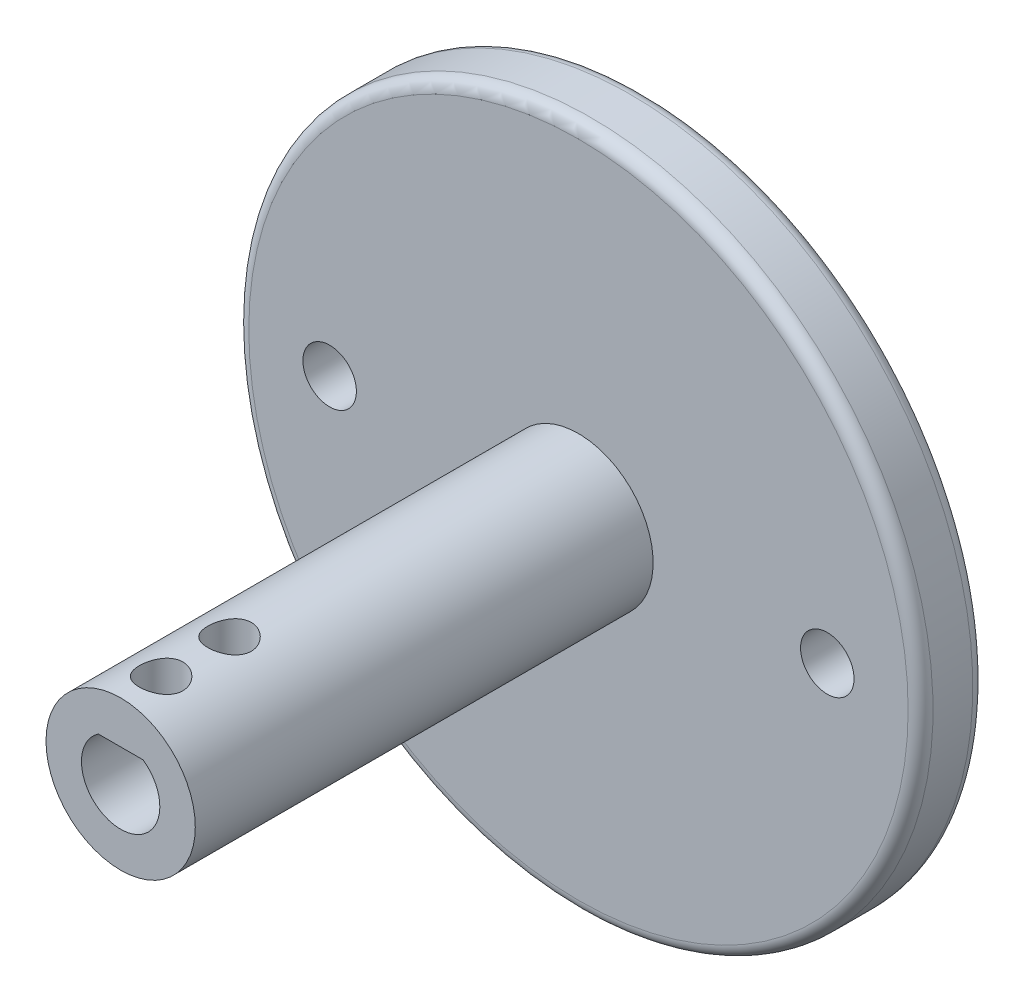
SolidWorks part; units mm, degrees
ref_plane "Alzado" through (0, 0, 0) normal (0, 0, 1) x (1, 0, 0)
ref_plane "Planta" through (0, 0, 0) normal (0, 1, 0) x (1, 0, 0)
ref_plane "Vista lateral" through (0, 0, 0) normal (1, 0, 0) x (0, 0, -1)
sketch "Croquis1" plane through (0, 0, 0) normal (0, 0, 1) x (1, 0, 0)
  line L0 (0, 0) -> (0, 2.5851) construction
  line L7 (-1.8, 2.5851) -> (1.8, 2.5851)
  circle A0 centre (0, 0) radius 6
  arc A1 (-1.8, 2.5851) -> (1.8, 2.5851) centre (0, 0) ccw
  point P14 (0, 2.5851)
  dimension "D2" = 6.3
  dimension "D1" = 12
  dimension "D3" = 3.6
extrude "Saliente-Extruir1" add sketch "Croquis1" along normal blind 40
sketch "Croquis2" plane through (0, 2.5851, 0) normal (0, 1, 0) x (1, 0, 0)
  line L0 (0, -40) -> (0, -36.75) construction
  line L2 (0, -36.75) -> (0, -35) construction
  line L3 (0, -35) -> (0, -33) construction
  line L4 (0, -33) -> (0, -31.25) construction
  line L5 (0, -31.25) -> (0, -28) construction
  line L6 (-6, -40) -> (6, -40) construction
  circle A0 centre (0, -36.75) radius 1.75
  circle A1 centre (0, -31.25) radius 1.75
  dimension "D1" = 3.5
  dimension "D2" = 12
  dimension "D3" = 2
extrude "Cortar-Extruir1" cut sketch "Croquis2" along normal blind 7.5
sketch "Croquis3" plane through (0, 0, 0) normal (0, 0, -1) x (-1, 0, 0)
  circle A0 centre (0, 0) radius 27.5
  dimension "D1" = 55
extrude "Saliente-Extruir2" add sketch "Croquis3" against normal blind 3.2 and the other way blind 2
sketch "Croquis5" plane through (0, 0, -2) normal (0, 0, -1) x (-1, 0, 0)
  line L0 (0, 0) -> (0, 7.5) construction
  line L1 (0, 7.5) -> (-7.5, 7.5) construction
  line L2 (0, 0) -> (-20, 0) construction
  circle A4 centre (-20, 0) radius 2.15
  circle A5 centre (0, 0) radius 27.5
  circle A6 centre (0, 0) radius 27.5
  circle A7 centre (20, 0) radius 2.15
  point P14 (0, 0)
  dimension "D8" = 4.3
  dimension "D1" = 7.5
  dimension "D2" = 7.5
  dimension "D7" = 20
  dimension "D6" = 0
extrude "Cortar-Extruir2" cut sketch "Croquis5" against normal blind 5.2 and the other way through all contours A4 | A7
fillet "Redondeo1" radius 1 2 edges at (-27.5, 0, -2) (-27.5, 0, 3.2)
